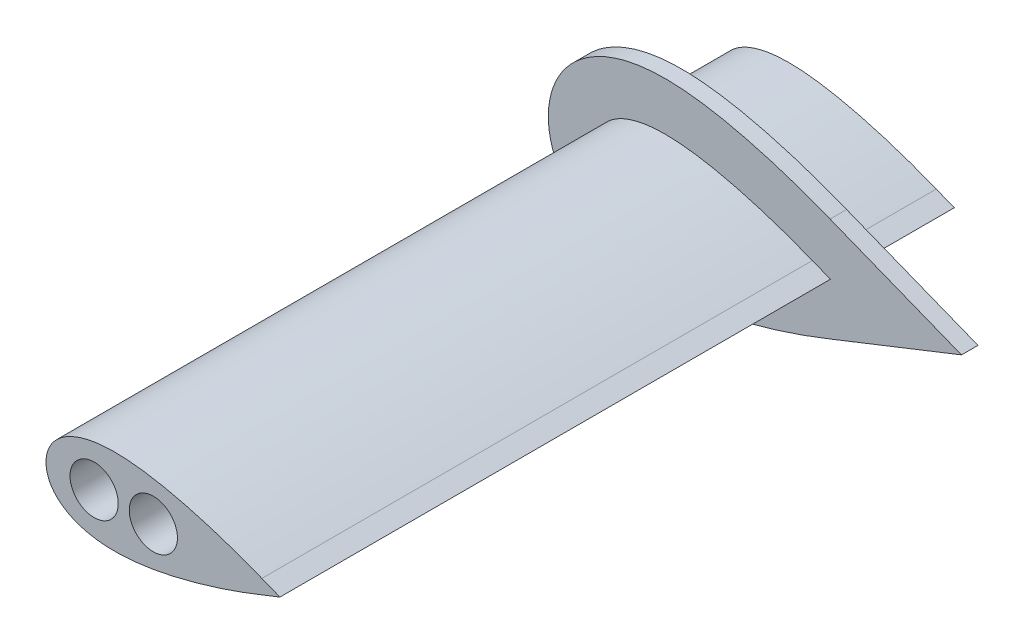
SolidWorks part; units mm, degrees
ref_plane "Front Plane" through (0, 0, 0) normal (0, 0, 1) x (1, 0, 0)
ref_plane "Top Plane" through (0, 0, 0) normal (0, 1, 0) x (1, 0, 0)
ref_plane "Right Plane" through (0, 0, 0) normal (1, 0, 0) x (0, 0, -1)
curve "Curve1"
  spline degree 3 poles (15, 0.0553, 0) (14.7504, 0.1555, 0) (14.2531, 0.3552, 0) (13.2557, 0.7272, 0) (12.0086, 1.1545, 0) (10.5081, 1.6108, 0) (9.0083, 2.0064, 0) (7.5085, 2.33, 0) (6.0074, 2.5603, 0) (4.7508, 2.6418, 0) (3.7477, 2.6098, 0) (2.9933, 2.5225, 0) (2.2339, 2.3534, 0) (1.6058, 2.116, 0) (1.1087, 1.8388, 0) (0.7182, 1.5477, 0) (0.3995, 1.204, 0) (0.0937, 0.6956, 0) (-0.0654, 0, 0) (0.0937, -0.6956, 0) (0.3995, -1.204, 0) (0.7182, -1.5477, 0) (1.1087, -1.8388, 0) (1.6058, -2.116, 0) (2.2339, -2.3534, 0) (2.9933, -2.5225, 0) (3.7477, -2.6098, 0) (4.7508, -2.6418, 0) (6.0074, -2.5603, 0) (7.5085, -2.33, 0) (9.0083, -2.0064, 0) (10.5081, -1.6108, 0) (12.0086, -1.1545, 0) (13.2557, -0.7272, 0) (14.2531, -0.3552, 0) (14.7504, -0.1555, 0) (15, -0.0553, 0) knots 0 0 0 0 0.024279 0.048376 0.096091 0.143261 0.189925 0.236074 0.281707 0.326919 0.349501 0.372229 0.39538 0.419578 0.432526 0.446653 0.463401 0.474441 0.5 0.525559 0.536599 0.553347 0.567474 0.580422 0.60462 0.627771 0.650499 0.673081 0.718293 0.763926 0.810075 0.856739 0.903909 0.951624 0.975721 1 1 1 1
sketch "Sketch2" plane through (0, 0, 0) normal (0, 0, 1) x (1, 0, 0)
  line L0 (-3.6652, 0) -> (26.3174, 0) construction
  line L3 (15.1863, 0.5193) -> (16.5, 0)
  line L4 (16.5, 0) -> (15.1863, -0.5193)
  circle A0 centre (3, 0) radius 1.75
  circle A1 centre (7.3, 0) radius 1.75
  spline S0 degree 3 poles (1175.8525, 2765.593) (51.6331, -48.1442) (38.5686, -8.715) (13.2557, 0.7272) (12.0086, 1.1545) (10.5081, 1.6108) (9.0083, 2.0064) (7.5085, 2.33) (6.0074, 2.5603) (4.7508, 2.6418) (3.7477, 2.6098) (2.9933, 2.5225) (2.2339, 2.3534) (1.6058, 2.116) (1.1087, 1.8388) (0.7182, 1.5477) (0.3995, 1.204) (0.0937, 0.6956) (-0.0654, 0) (0.0937, -0.6956) (0.3995, -1.204) (0.7182, -1.5477) (1.1087, -1.8388) (1.6058, -2.116) (2.2339, -2.3534) (2.9933, -2.5225) (3.7477, -2.6098) (4.7508, -2.6418) (6.0074, -2.5603) (7.5085, -2.33) (9.0083, -2.0064) (10.5081, -1.6108) (12.0086, -1.1545) (13.2557, -0.7272) (38.5686, 8.715) (51.633, 48.1441) (1175.8507, -2765.5885) knots -2.34259 -2.34259 -2.34259 -2.34259 0.024279 0.048376 0.096091 0.143261 0.189925 0.236074 0.281707 0.326919 0.349501 0.372229 0.39538 0.419578 0.432526 0.446653 0.463401 0.474441 0.5 0.525559 0.536599 0.553347 0.567474 0.580422 0.60462 0.627771 0.650499 0.673081 0.718293 0.763926 0.810075 0.856739 0.903909 0.951624 0.975721 3.342589 3.342589 3.342589 3.342589 only from (15, 0.0553) to (15, -0.0553) construction
  spline S1 degree 3 poles (15, 0.0553) (14.7504, 0.1555) (14.2531, 0.3552) (13.2557, 0.7272) (12.0086, 1.1545) (10.5081, 1.6108) (9.0083, 2.0064) (7.5085, 2.33) (6.0074, 2.5603) (4.7508, 2.6418) (3.7477, 2.6098) (2.9933, 2.5225) (2.2339, 2.3534) (1.6058, 2.116) (1.1087, 1.8388) (0.7182, 1.5477) (0.3995, 1.204) (0.0937, 0.6956) (-0.0654, 0) (0.0937, -0.6956) (0.3995, -1.204) (0.7182, -1.5477) (1.1087, -1.8388) (1.6058, -2.116) (2.2339, -2.3534) (2.9933, -2.5225) (3.7477, -2.6098) (4.7508, -2.6418) (6.0074, -2.5603) (7.5085, -2.33) (9.0083, -2.0064) (10.5081, -1.6108) (12.0086, -1.1545) (13.2557, -0.7272) (14.2531, -0.3552) (14.7504, -0.1555) (15, -0.0553) knots 0 0 0 0 0.024279 0.048376 0.096091 0.143261 0.189925 0.236074 0.281707 0.326919 0.349501 0.372229 0.39538 0.419578 0.432526 0.446653 0.463401 0.474441 0.5 0.525559 0.536599 0.553347 0.567474 0.580422 0.60462 0.627771 0.650499 0.673081 0.718293 0.763926 0.810075 0.856739 0.903909 0.951624 0.975721 1 1 1 1 construction
  spline S2 degree 1 poles (15.1863, 0.5193) (15.1863, -0.5193) knots 0 0 1 1 construction
  spline S3 degree 3 poles (15.1863, 0.5193) (13.8877, 1.0407) (11.9078, 1.7439) (9.2024, 2.4831) (7.1345, 2.9201) (5.0094, 3.1697) (3.1858, 3.1074) (1.7237, 2.7318) (0.6739, 2.212) (-0.2382, 1.3258) (-0.6309, 0) (-0.2382, -1.3258) (0.6739, -2.212) (1.7237, -2.7318) (3.1858, -3.1074) (5.0094, -3.1697) (7.1345, -2.9201) (9.2024, -2.4831) (11.9078, -1.7439) (13.8877, -1.0407) (15.1863, -0.5193) knots 0 0 0 0 0.125 0.1875 0.25 0.3125 0.375 0.40625 0.4375 0.46875 0.5 0.53125 0.5625 0.59375 0.625 0.6875 0.75 0.8125 0.875 1 1 1 1
  dimension "D1" = 0.5
  dimension "D2" = 16.5
  dimension "D4" = 3.5
  dimension "D5" = 3.5
  dimension "D6" = 3
  dimension "D7" = 4.3
extrude "Boss-Extrude2" add sketch "Sketch2" along normal blind 40
sketch "Sketch3" plane through (0, 0, 0) normal (0, 0, -1) x (-1, 0, 0)
  line L4 (-16.4729, 3.7742) -> (-26.0209, 0)
  line L5 (-26.0209, 0) -> (-16.4902, -3.7673)
  line L6 (-16.4729, 3.7742) -> (-26.0209, 0)
  line L7 (-26.0209, 0) -> (-16.4902, -3.7673)
  line L8 (-16.5, 0) -> (-15.1863, -0.5193)
  line L9 (-15.1863, 0.5193) -> (-16.5, 0)
  line L10 (-16.5, 0) -> (-15.1863, -0.5193)
  line L11 (-15.1863, 0.5193) -> (-16.5, 0)
  spline S2 degree 3 poles (-1134.7619, -2777.121) (-104.4698, 378.8982) (-106.7135, 19.3696) (-9.741, -5.9446) (-8.7506, -6.1671) (-6.7379, -6.5009) (-5.7275, -6.6096) (-4.2022, -6.6324) (-3.689, -6.6151) (-2.678, -6.5182) (-2.1798, -6.4394) (-1.1999, -6.2117) (-0.7184, -6.0624) (-0.0118, -5.7726) (0.2225, -5.6641) (0.6763, -5.4261) (0.896, -5.2967) (1.3206, -5.0163) (1.5256, -4.8655) (1.9197, -4.541) (2.11, -4.3659) (2.6439, -3.8124) (2.9501, -3.4085) (3.3297, -2.7464) (3.4436, -2.5148) (3.6405, -2.0398) (3.723, -1.7983) (3.857, -1.3075) (3.9084, -1.0582) (3.9791, -0.5515) (3.9981, -0.2925) (4.003, 0.4752) (3.939, 0.9801) (3.7452, 1.7273) (3.6646, 1.9722) (3.475, 2.4458) (3.3657, 2.6759) (3.1175, 3.1221) (2.9775, 3.3396) (2.6725, 3.7532) (2.5083, 3.9488) (2.1581, 4.3192) (1.9721, 4.494) (1.5795, 4.8239) (1.3726, 4.9791) (0.7354, 5.4074) (0.2845, 5.6467) (-0.4263, 5.9443) (-0.6681, 6.0329) (-1.1539, 6.1889) (-1.399, 6.2566) (-2.1399, 6.4322) (-2.6413, 6.5131) (-3.6569, 6.6133) (-4.1714, 6.6317) (-5.6972, 6.6119) (-6.704, 6.5049) (-8.705, 6.1761) (-9.7018, 5.9538) (-105.4212, -18.9441) (-96.6874, -367.6664) (-1195.383, 2752.2714) knots -5.994617 -5.994617 -5.994617 -5.994617 0.125 0.125 0.1875 0.1875 0.25 0.25 0.28125 0.28125 0.3125 0.3125 0.34375 0.34375 0.359375 0.359375 0.375 0.375 0.390625 0.390625 0.40625 0.40625 0.4375 0.4375 0.453125 0.453125 0.46875 0.46875 0.484375 0.484375 0.5 0.5 0.53125 0.53125 0.546875 0.546875 0.5625 0.5625 0.578125 0.578125 0.59375 0.59375 0.609375 0.609375 0.625 0.625 0.65625 0.65625 0.671875 0.671875 0.6875 0.6875 0.71875 0.71875 0.75 0.75 0.8125 0.8125 0.875 0.875 6.886534 6.886534 6.886534 6.886534 only from (-16.4902, -3.7673) to (-16.4729, 3.7742)
  spline S3 degree 3 poles (-16.4902, -3.7673) (-14.6018, -4.5255) (-12.6821, -5.1769) (-9.741, -5.9446) (-8.7506, -6.1671) (-6.7379, -6.5009) (-5.7275, -6.6096) (-4.2022, -6.6324) (-3.689, -6.6151) (-2.678, -6.5182) (-2.1798, -6.4394) (-1.1999, -6.2117) (-0.7184, -6.0624) (-0.0118, -5.7726) (0.2225, -5.6641) (0.6763, -5.4261) (0.896, -5.2967) (1.3206, -5.0163) (1.5256, -4.8655) (1.9197, -4.541) (2.11, -4.3659) (2.6439, -3.8124) (2.9501, -3.4085) (3.3297, -2.7464) (3.4436, -2.5148) (3.6405, -2.0398) (3.723, -1.7983) (3.857, -1.3075) (3.9084, -1.0582) (3.9791, -0.5515) (3.9981, -0.2925) (4.003, 0.4752) (3.939, 0.9801) (3.7452, 1.7273) (3.6646, 1.9722) (3.475, 2.4458) (3.3657, 2.6759) (3.1175, 3.1221) (2.9775, 3.3396) (2.6725, 3.7532) (2.5083, 3.9488) (2.1581, 4.3192) (1.9721, 4.494) (1.5795, 4.8239) (1.3726, 4.9791) (0.7354, 5.4074) (0.2845, 5.6467) (-0.4263, 5.9443) (-0.6681, 6.0329) (-1.1539, 6.1889) (-1.399, 6.2566) (-2.1399, 6.4322) (-2.6413, 6.5131) (-3.6569, 6.6133) (-4.1714, 6.6317) (-5.6972, 6.6119) (-6.704, 6.5049) (-8.705, 6.1761) (-9.7018, 5.9538) (-12.6566, 5.1853) (-14.5817, 4.5328) (-16.4729, 3.7742) knots 0 0 0 0 0.125 0.125 0.1875 0.1875 0.25 0.25 0.28125 0.28125 0.3125 0.3125 0.34375 0.34375 0.359375 0.359375 0.375 0.375 0.390625 0.390625 0.40625 0.40625 0.4375 0.4375 0.453125 0.453125 0.46875 0.46875 0.484375 0.484375 0.5 0.5 0.53125 0.53125 0.546875 0.546875 0.5625 0.5625 0.578125 0.578125 0.59375 0.59375 0.609375 0.609375 0.625 0.625 0.65625 0.65625 0.671875 0.671875 0.6875 0.6875 0.71875 0.71875 0.75 0.75 0.8125 0.8125 0.875 0.875 1 1 1 1
  spline S4 degree 3 poles (-142.7461, -2995.4058) (-93.2642, 339.4113) (-99.8039, 22.2702) (-9.2024, -2.4831) (-7.1345, -2.9201) (-5.0094, -3.1697) (-3.1858, -3.1074) (-1.7237, -2.7318) (-0.6739, -2.212) (0.2382, -1.3258) (0.6309, 0) (0.2382, 1.3258) (-0.6739, 2.212) (-1.7237, 2.7318) (-3.1858, 3.1074) (-5.0094, 3.1697) (-7.1345, 2.9201) (-9.2024, 2.4831) (-99.8041, -22.2702) (-93.2642, -339.4127) (-142.7465, 2995.428) knots -8.122509 -8.122509 -8.122509 -8.122509 0.125 0.1875 0.25 0.3125 0.375 0.40625 0.4375 0.46875 0.5 0.53125 0.5625 0.59375 0.625 0.6875 0.75 0.8125 0.875 9.122527 9.122527 9.122527 9.122527 only from (-15.1863, -0.5193) to (-15.1863, 0.5193)
  spline S5 degree 3 poles (-15.1863, -0.5193) (-13.8877, -1.0407) (-11.9078, -1.7439) (-9.2024, -2.4831) (-7.1345, -2.9201) (-5.0094, -3.1697) (-3.1858, -3.1074) (-1.7237, -2.7318) (-0.6739, -2.212) (0.2382, -1.3258) (0.6309, 0) (0.2382, 1.3258) (-0.6739, 2.212) (-1.7237, 2.7318) (-3.1858, 3.1074) (-5.0094, 3.1697) (-7.1345, 2.9201) (-9.2024, 2.4831) (-11.9078, 1.7439) (-13.8877, 1.0407) (-15.1863, 0.5193) knots 0 0 0 0 0.125 0.1875 0.25 0.3125 0.375 0.40625 0.4375 0.46875 0.5 0.53125 0.5625 0.59375 0.625 0.6875 0.75 0.8125 0.875 1 1 1 1
  dimension "D1" = 3.5
  dimension "D2" = 0
extrude "Boss-Extrude3" add sketch "Sketch3" along normal blind 1.2
sketch "Sketch4" plane through (0, 0, 0) normal (0, 0, -1) x (-1, 0, 0)
  line L0 (-16.5, 0) -> (-15.1863, 0.5193) construction
  line L1 (-15.1863, -0.5193) -> (-16.5, 0) construction
  line L2 (-16.5, 0) -> (-15.1863, 0.5193)
  line L3 (-15.1863, -0.5193) -> (-16.5, 0)
  circle A0 centre (-7.3, 0) radius 1.75 construction
  circle A1 centre (-3, 0) radius 1.75 construction
  circle A2 centre (-7.3, 0) radius 1.75
  circle A3 centre (-3, 0) radius 1.75
  spline S0 degree 3 poles (-142.7461, 2995.4058) (-93.2642, -339.4113) (-99.8039, -22.2702) (-9.2024, 2.4831) (-7.1345, 2.9201) (-5.0094, 3.1697) (-3.1858, 3.1074) (-1.7237, 2.7318) (-0.6739, 2.212) (0.2382, 1.3258) (0.6309, 0) (0.2382, -1.3258) (-0.6739, -2.212) (-1.7237, -2.7318) (-3.1858, -3.1074) (-5.0094, -3.1697) (-7.1345, -2.9201) (-9.2024, -2.4831) (-99.8041, 22.2702) (-93.2642, 339.4127) (-142.7465, -2995.428) knots -8.122509 -8.122509 -8.122509 -8.122509 0.125 0.1875 0.25 0.3125 0.375 0.40625 0.4375 0.46875 0.5 0.53125 0.5625 0.59375 0.625 0.6875 0.75 0.8125 0.875 9.122527 9.122527 9.122527 9.122527 only from (-15.1863, 0.5193) to (-15.1863, -0.5193) construction
  spline S1 degree 3 poles (-15.1863, 0.5193) (-13.8877, 1.0407) (-11.9078, 1.7439) (-9.2024, 2.4831) (-7.1345, 2.9201) (-5.0094, 3.1697) (-3.1858, 3.1074) (-1.7237, 2.7318) (-0.6739, 2.212) (0.2382, 1.3258) (0.6309, 0) (0.2382, -1.3258) (-0.6739, -2.212) (-1.7237, -2.7318) (-3.1858, -3.1074) (-5.0094, -3.1697) (-7.1345, -2.9201) (-9.2024, -2.4831) (-11.9078, -1.7439) (-13.8877, -1.0407) (-15.1863, -0.5193) knots 0 0 0 0 0.125 0.1875 0.25 0.3125 0.375 0.40625 0.4375 0.46875 0.5 0.53125 0.5625 0.59375 0.625 0.6875 0.75 0.8125 0.875 1 1 1 1
extrude "Boss-Extrude4" add sketch "Sketch4" along normal blind 9
